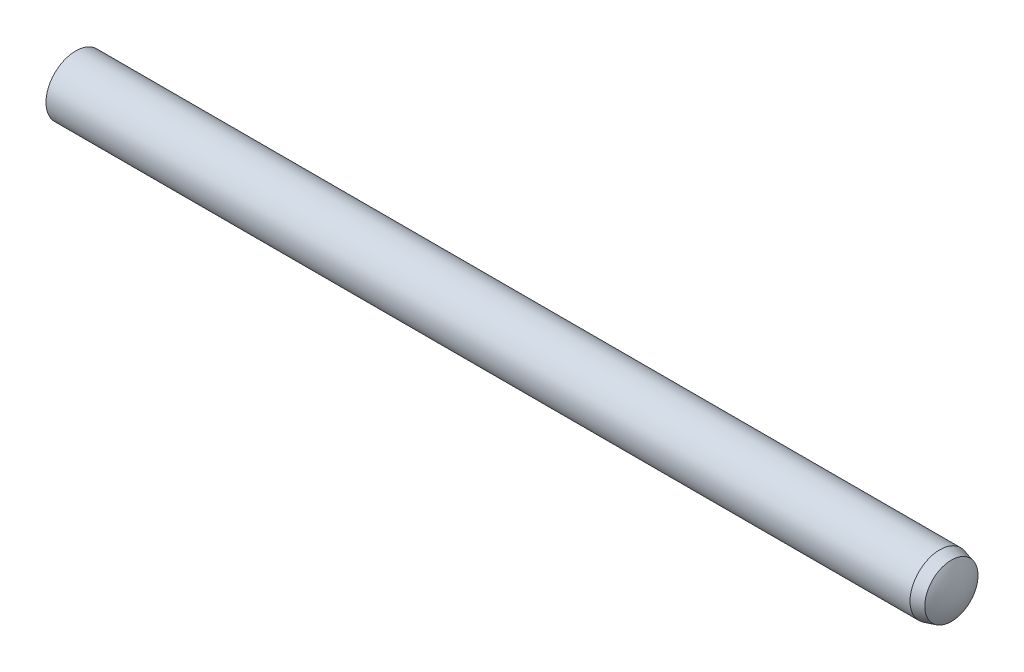
SolidWorks part; units mm, degrees
material "AISI Type 316L stainless steel"
ref_plane "Front Plane" through (0, 0, 0) normal (0, 0, 1) x (1, 0, 0)
ref_plane "Top Plane" through (0, 0, 0) normal (0, 1, 0) x (1, 0, 0)
ref_plane "Right Plane" through (0, 0, 0) normal (1, 0, 0) x (0, 0, -1)
sketch "Sketch1" plane through (0, 0, 0) normal (0, 0, 1) x (1, 0, 0)
  line L0 (-22.5, 0) -> (22.5, 0) construction
  line L1 (22.5, 1.5) -> (22.5, -1.5) construction
  line L2 (-22.5, 1.5) -> (-22.5, -1.5) construction
  line L3 (21.525, 1.5) -> (21.525, -1.5) construction
  line L4 (-22.05, 1.5) -> (-22.05, -1.5) construction
  line L5 (-22.5, 0) -> (-22.05, 0) construction
  line L6 (22.5, 0) -> (21.525, 0) construction
  line L7 (22.11, 1.5) -> (22.11, -1.5) construction
  dimension "Dia" = 3
  dimension "Length" = 45
  dimension "D1" = 0.975
  dimension "D2" = 0.45
  dimension "D3" = 0.585
sketch "Sketch2" plane through (0, 0, 0) normal (1, 0, 0) x (0, 0, -1)
  circle A0 centre (0, 0) radius 1.5
extrude "Extrude1" add sketch "Sketch2" against normal up to vertex (22.5 mm away) and the other way up to vertex (22.5 mm away) up to point (-22.5, 0, 0) other way up to point (22.5, 0, 0)
sketch "Sketch5" plane through (0, 0, 0) normal (0, 0, 1) x (1, 0, 0)
  line L0 (21.525, 1.5) -> (21.525, 2)
  line L1 (21.525, 2) -> (23, 2)
  line L2 (23, 2) -> (23, 0)
  line L3 (22.5, 0) -> (23, 0)
  line L5 (-22.05, 1.5) -> (-22.05, 2)
  line L6 (-22.05, 2) -> (-23, 2)
  line L7 (-23, 2) -> (-23, 0)
  line L8 (21.525, 1.5) -> (22.11, 1.3432)
  line L10 (-22.5, 0) -> (-23, 0)
  line L11 (-22.5, 1.5) -> (-22.5, -1.5) construction
  line L13 (21.525, 1.5) -> (21.525, -1.5) construction
  line L15 (-22.5, 0) -> (22.5, 0) construction
  line L16 (22.11, 1.5) -> (22.11, -1.5) construction
  line L17 (22.5, 1.5) -> (22.5, -1.5) construction
  arc A0 (22.11, 1.3432) -> (22.5, 0) centre (19.9918, 0) cw
  arc A1 (-22.05, 1.5) -> (-22.5, 0) centre (-19.775, 0) ccw
  dimension "D1" = 15
  dimension "D2" = 0.5
revolve "Cut-Revolve1" cut sketch "Sketch5" angle 360 about L0
equation "\"D1@Sketch1\" = \"Dia@Sketch1\"*.325"
equation "\"D2@Sketch1\" = \"Dia@Sketch1\"*.15"
equation "\"D3@Sketch1\" = \"D1@Sketch1\"*.6"
